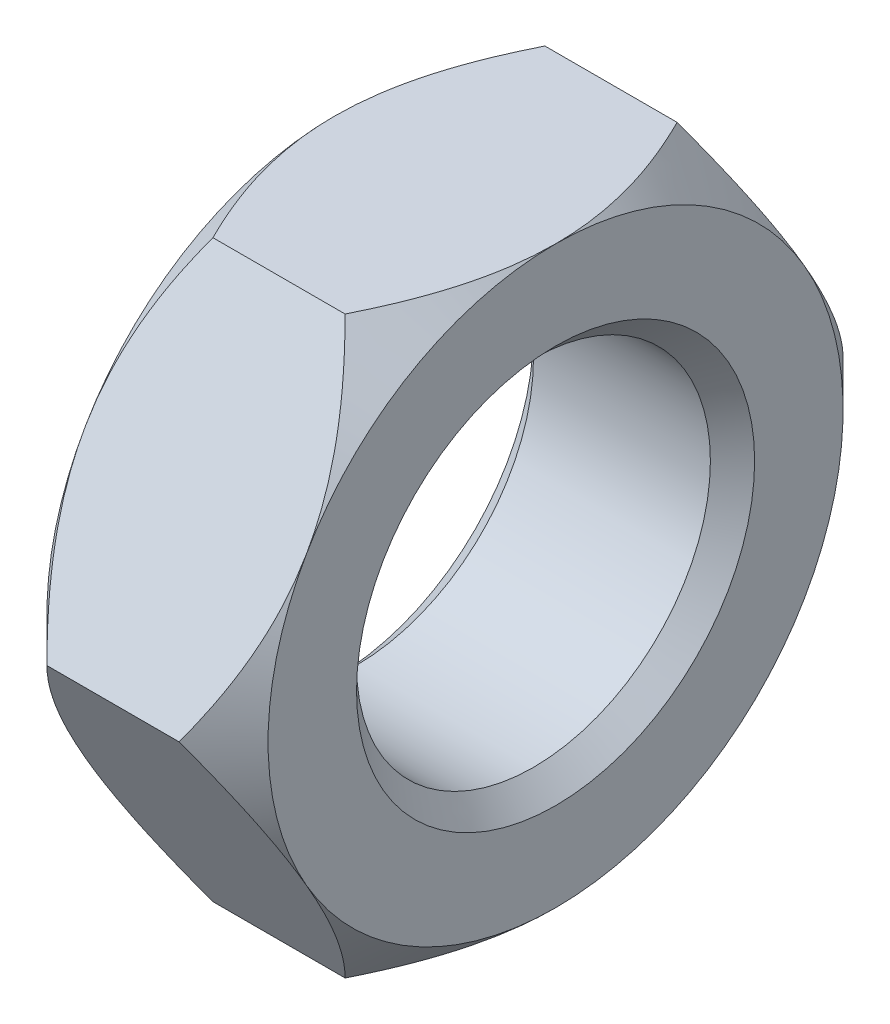
SolidWorks part; units mm, degrees
ref_plane "前视基准面" through (0, 0, 0) normal (0, 0, 1) x (1, 0, 0)
ref_plane "上视基准面" through (0, 0, 0) normal (0, 1, 0) x (1, 0, 0)
ref_plane "右视基准面" through (0, 0, 0) normal (1, 0, 0) x (0, 0, -1)
sketch "草图1" plane through (0, 0, 0) normal (1, 0, 0) x (0, 0, -1)
  line L0 (0, 0) -> (-7.5056, -13) construction
  line L1 (-7.5056, -13) -> (7.5056, -13)
  line L2 (7.5056, -13) -> (0, 0) construction
  line L3 (-15.0111, 0) -> (-7.5056, -13)
  line L4 (-7.5056, 13) -> (-15.0111, 0)
  line L5 (7.5056, 13) -> (-7.5056, 13)
  line L6 (15.0111, 0) -> (7.5056, 13)
  line L7 (7.5056, -13) -> (15.0111, 0)
  point P16 (0, 0)
  dimension "D1" = 6
  dimension "D2" = 26
extrude "凸台-拉伸1" add sketch "草图1" along normal blind 10
sketch "草图2" plane through (10, 0, 0) normal (1, 0, 0) x (0, 0, -1)
  circle A0 centre (0, 0) radius 8
  dimension "D1" = 16
extrude "切除-拉伸1" cut sketch "草图2" against normal blind 20
chamfer "倒角1" distance 1 angle 45 2 edges at (0, 0, -8) (10, 0, -8)
sketch "草图3" plane through (10, 0, 0) normal (1, 0, 0) x (0, 0, -1)
  circle A0 centre (0, 0) radius 13
  dimension "D1" = 26
extrude "切除-拉伸2" cut sketch "草图3" against normal blind 45 draft 45 flip side to cut
sketch "草图4" plane through (0, 0, 0) normal (-1, 0, 0) x (0, 0, 1)
  circle A0 centre (0, 0) radius 13
  dimension "D1" = 26
extrude "切除-拉伸3" cut sketch "草图4" against normal blind 45 draft 45 flip side to cut
